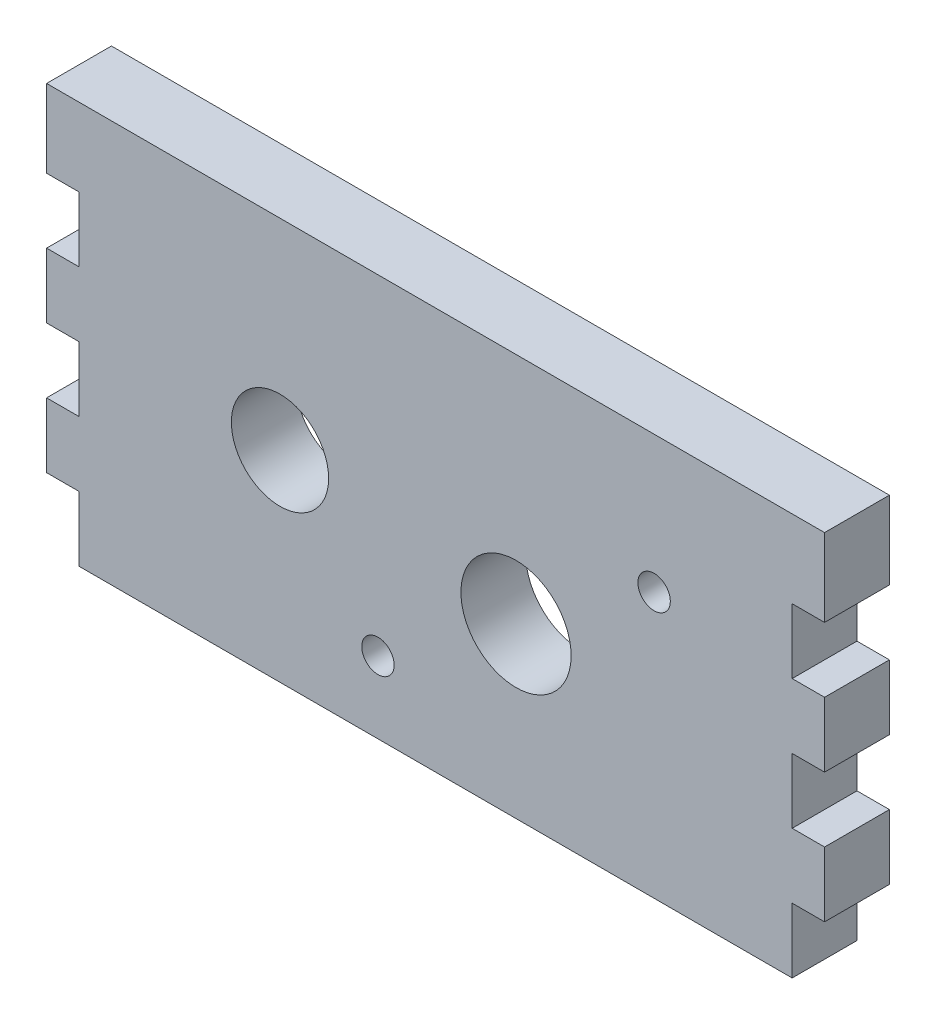
SolidWorks part; units mm, degrees
ref_plane "정면" through (0, 0, 0) normal (0, 0, 1) x (1, 0, 0)
ref_plane "윗면" through (0, 0, 0) normal (0, 1, 0) x (1, 0, 0)
ref_plane "우측면" through (0, 0, 0) normal (1, 0, 0) x (0, 0, -1)
sketch "스케치2" plane through (0, 0, 0) normal (0, 0, 1) x (1, 0, 0)
  line L0 (-6.0717, -5) -> (65.5766, -5) construction
  line L1 (-60, -31) -> (60, -31)
  line L2 (-60, -31) -> (-60, 31)
  line L3 (-60, 31) -> (60, 31)
  line L4 (60, -31) -> (60, 31)
  line L5 (-60, -31) -> (60, 31) construction
  line L6 (-60, 31) -> (60, -31) construction
  line L7 (-15.8273, -24.7708) -> (37.7136, 12.7189) construction
  circle A0 centre (12.4083, -5) radius 8.5
  circle A1 centre (-24, 0) radius 7.5
  circle A2 centre (33.7062, 9.913) radius 2.5
  circle A3 centre (-8.8897, -19.913) radius 2.5
  point P0 (0, 0)
  dimension "D5" = 17
  dimension "D8" = 15
  dimension "D9" = 35
  dimension "D10" = 5
  dimension "D1" = 62
  dimension "D2" = 120
  dimension "D3" = 36.75
  dimension "D4" = 36
  dimension "D6" = 31
  dimension "D7" = 36
  dimension "D11" = 26
  dimension "D12" = 26
extrude "보스-돌출1" add sketch "스케치2" along normal blind 10 contours L1 L4 L3 L2 A1 A0
sketch "스케치3" plane through (0, 0, 10) normal (0, 0, 1) x (1, 0, 0)
  line L0 (-60, -31) -> (-60, 31) construction
  line L1 (-60, -21) -> (-55, -21)
  line L2 (-60, -21) -> (-60, -31)
  line L3 (-60, -31) -> (-55, -31)
  line L4 (-55, -21) -> (-55, -31)
  line L5 (-60, -31) -> (60, -31) construction
  dimension "D1" = 5
  dimension "D2" = 10
extrude "컷-돌출1" cut sketch "스케치3" against normal up to next
pattern_linear "선형 패턴1" count 3 spacing 20 along (0, 1, 0) of "컷-돌출1"
mirror "대칭 복사1" about plane through (0, 0, 0) normal (1, 0, 0) of "선형 패턴1", "컷-돌출1"
